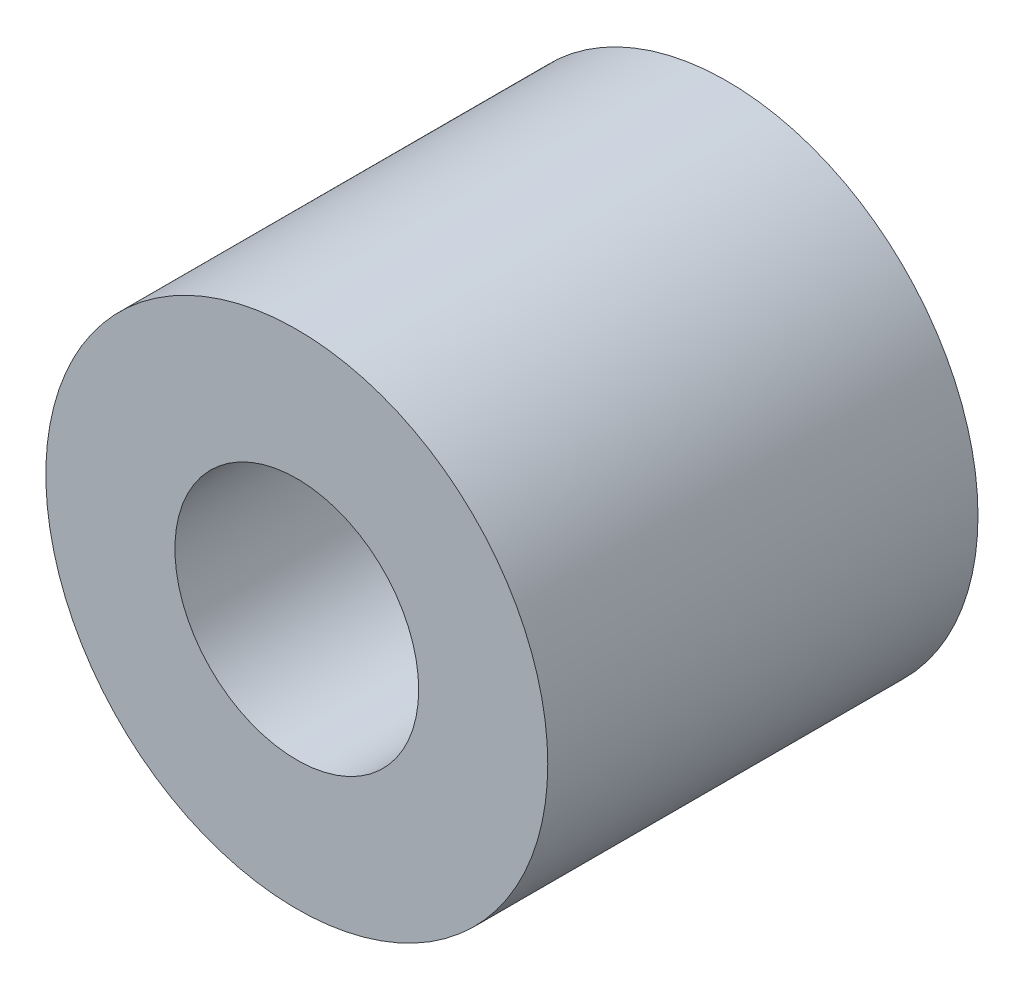
SolidWorks part; units mm, degrees
ref_plane "Front Plane" through (0, 0, 0) normal (0, 0, 1) x (1, 0, 0)
ref_plane "Top Plane" through (0, 0, 0) normal (0, 1, 0) x (1, 0, 0)
ref_plane "Right Plane" through (0, 0, 0) normal (1, 0, 0) x (0, 0, -1)
sketch "Sketch1" plane through (0, 0, 0) normal (0, 0, 1) x (1, 0, 0)
  circle A0 centre (0, 0) radius 1.7
  circle A1 centre (0, 0) radius 3.5
  dimension "D1" = 3.4
  dimension "D2" = 7
extrude "Boss-Extrude1" add sketch "Sketch1" along normal blind 6
